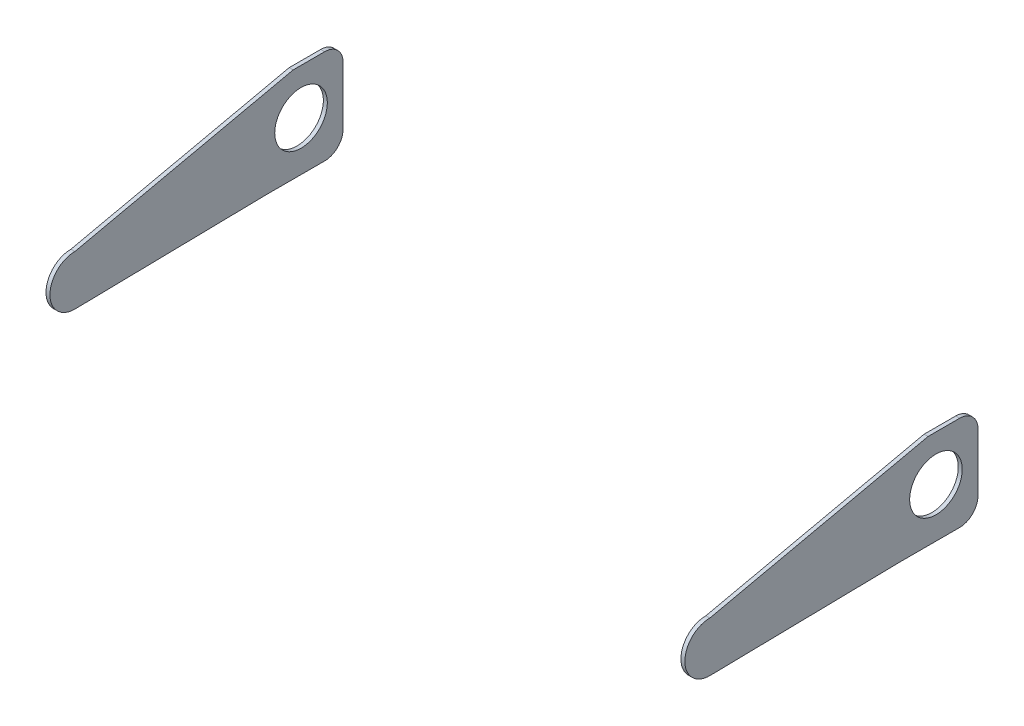
SolidWorks part; units mm, degrees
ref_plane "Front Plane" through (0, 0, 0) normal (0, 0, 1) x (1, 0, 0)
ref_plane "Top Plane" through (0, 0, 0) normal (0, 1, 0) x (1, 0, 0)
ref_plane "Right Plane" through (0, 0, 0) normal (1, 0, 0) x (0, 0, -1)
ref_plane "Plane2" through (-120, 0, 0) normal (-1, 0, 0) x (0, 0, 1)
sketch "Sketch1" plane through (-120, 0, 0) normal (-1, 0, 0) x (0, 0, 1)
  line L0 (-8.5, -10.5) -> (30.5, -10.5) construction
  line L1 (11, -20) -> (-61.8571, -18.7)
  line L3 (11, -1) -> (11, -20) construction
  line L8 (-72, 17.3) -> (11, -1)
  line L9 (-100, -19.2) -> (-50, -19.2) construction
  line L10 (-61.8571, -18.7) -> (-84, -18.7)
  line L12 (-72, 17.3) -> (-84, 17.3)
  line L13 (-91, -11.7) -> (-91, 10.3)
  line L14 (-89.0096, 15.1891) -> (-91, 17.3) construction
  line L16 (-100, 24) -> (-100, -19.2) construction
  line L17 (-91, -11.7087) -> (-91, -18.7) construction
  arc A1 (11, -20) -> (11, -1) centre (11, -10.5) ccw
  circle A5 centre (11, -10.5) radius 8.5 construction
  arc A6 (-84, 17.3) -> (-91, 10.3) centre (-84, 10.3) ccw
  arc A7 (-84, -18.7) -> (-91, -11.7) centre (-84, -11.7) cw
  circle A8 centre (-75, 0) radius 10
  circle A9 centre (-75, 0) radius 10 construction
  point P9 (-75, 0)
  point P10 (-49.0475, 10.6135)
  point P13 (-75, 0)
  dimension "D1" = 19
  dimension "D2" = 7
  dimension "D5" = 17
  dimension "D4" = 7
  dimension "D6" = 36
  dimension "D7" = 0.5
  dimension "D8" = 12
  dimension "D9" = 9
extrude "Boss-Extrude1" add sketch "Sketch1" along normal blind 1.5
mirror "Mirror2" about plane through (0, 0, 0) normal (1, 0, 0) of bodies 101
